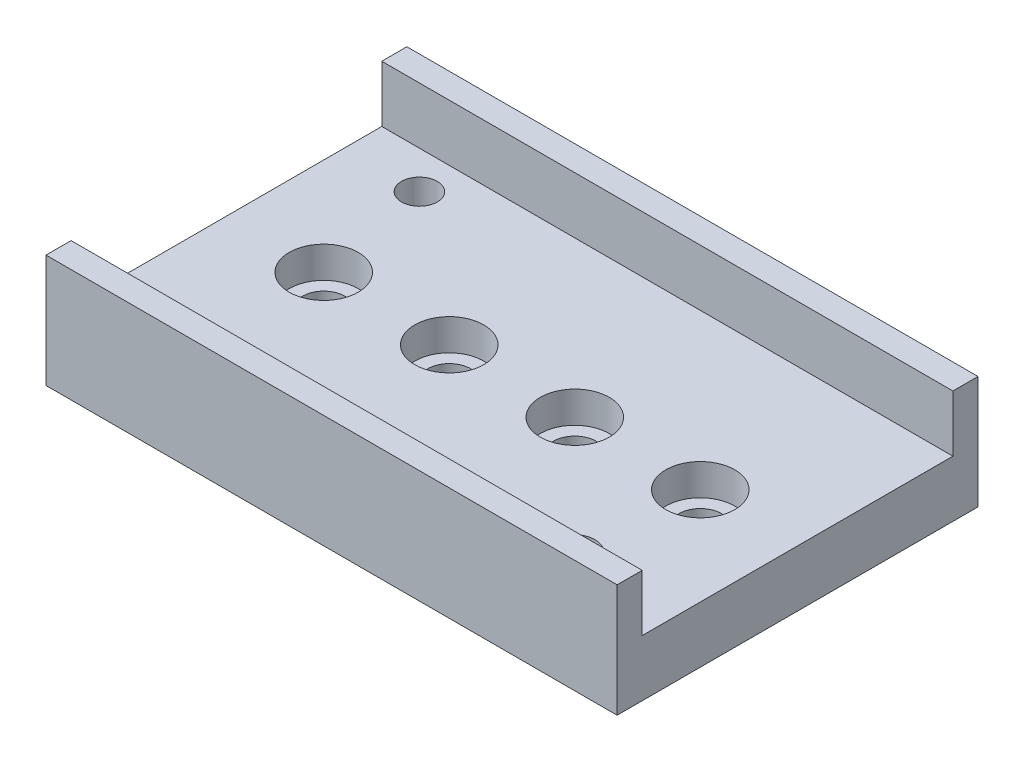
SolidWorks part; units mm, degrees
ref_plane "Front Plane" through (0, 0, 0) normal (0, 0, 1) x (1, 0, 0)
ref_plane "Top Plane" through (0, 0, 0) normal (0, 1, 0) x (1, 0, 0)
ref_plane "Right Plane" through (0, 0, 0) normal (1, 0, 0) x (0, 0, -1)
sketch "Sketch1" plane through (0, 0, 0) normal (0, 1, 0) x (1, 0, 0)
  line L0 (-22.75, 14.375) -> (22.75, 14.375)
  line L1 (-20.75, -12.375) -> (20.75, -12.375)
  line L2 (-20.75, -12.375) -> (-20.75, 12.375)
  line L3 (-20.75, 12.375) -> (20.75, 12.375)
  line L4 (20.75, -12.375) -> (20.75, 12.375)
  line L5 (-20.75, -12.375) -> (20.75, 12.375) construction
  line L6 (-20.75, 12.375) -> (20.75, -12.375) construction
  line L7 (22.75, -14.375) -> (22.75, 14.375)
  line L8 (-22.75, -14.375) -> (22.75, -14.375)
  line L9 (-22.75, -14.375) -> (-22.75, 14.375)
  circle A1 centre (-15, 0) radius 1.7
  circle A2 centre (-5, 0) radius 1.7
  circle A3 centre (5, 0) radius 1.7
  circle A4 centre (15, 0) radius 1.7
  point P0 (0, 0)
  dimension "D4" = 3.4
  dimension "D5" = 7.75
  dimension "D7" = 10
  dimension "D1" = 24.75
  dimension "D2" = 41.5
  dimension "D3" = 2
  dimension "D6" = 4
extrude "Boss-Extrude1" add sketch "Sketch1" along normal blind 2 contours L1 L4 L3 L2 | L9 L8 L7 L0 L4 L1 L2 L3
sketch "Sketch2" plane through (0, 2, 0) normal (0, 1, 0) x (1, 0, 0)
  line L1 (-22.75, -14.375) -> (22.75, -14.375) construction
  line L2 (-22.75, 14.375) -> (22.75, 14.375)
  line L3 (-22.75, 14.375) -> (-22.75, 12.375)
  line L4 (-22.75, -14.375) -> (22.75, -14.375)
  line L5 (22.75, 14.375) -> (22.75, 12.375)
  line L6 (22.75, -14.375) -> (22.75, 14.375) construction
  line L8 (-20.75, -12.375) -> (20.75, -12.375)
  line L10 (-20.75, 12.375) -> (20.75, 12.375)
  line L11 (-20.75, 12.375) -> (-22.75, 12.375)
  line L12 (-20.75, -12.375) -> (-22.75, -12.375)
  line L13 (-22.75, -12.375) -> (-22.75, -14.375)
  line L14 (-22.75, 14.375) -> (-22.75, -14.375) construction
  line L15 (-20.75, 12.375) -> (-20.75, -12.375) construction
  line L16 (20.75, 12.375) -> (22.75, 12.375)
  line L17 (20.75, -12.375) -> (22.75, -12.375)
  line L18 (22.75, -12.375) -> (22.75, -14.375)
  line L19 (20.75, 12.375) -> (20.75, -12.375) construction
  line L20 (22.75, 14.375) -> (22.75, -14.375) construction
  dimension "D1" = 2
extrude "Boss-Extrude2" add sketch "Sketch2" along normal blind 7
sketch "Sketch3" plane through (0, 2, 0) normal (0, 1, 0) x (1, 0, 0)
  line L0 (22.75, -12.375) -> (22.75, 12.375) construction
  line L1 (-22.75, 12.375) -> (22.75, 12.375)
  line L2 (-22.75, 12.375) -> (-22.75, 4.375)
  line L3 (-22.75, 4.375) -> (22.75, 4.375)
  line L4 (22.75, 12.375) -> (22.75, 4.375)
  line L6 (-22.75, -12.375) -> (22.75, -12.375)
  line L7 (-22.75, -12.375) -> (-22.75, -4.375)
  line L8 (-22.75, -4.375) -> (22.75, -4.375)
  line L9 (22.75, -12.375) -> (22.75, -4.375)
  line L12 (-22.75, 4.375) -> (22.75, 4.375)
  line L13 (-22.75, 4.375) -> (-22.75, -4.375)
  line L14 (-22.75, 0) -> (22.75, 0) construction
  line L15 (-22.75, -12.375) -> (-22.75, 12.375) construction
  line L16 (-22.75, -4.375) -> (22.75, -4.375)
  line L17 (22.75, 4.375) -> (22.75, -4.375)
  circle A2 centre (-16.75, 9.375) radius 1.425
  circle A3 centre (14.25, -9.325) radius 1.685
  circle A5 centre (-15, 0) radius 2.75
  circle A6 centre (-5, 0) radius 2.75
  circle A7 centre (5, 0) radius 2.75
  circle A8 centre (15, 0) radius 2.75
  line M22 (-22.75, 12.375) -> (-22.75, -12.375)
  line M23 (-22.75, -12.375) -> (22.75, -12.375)
  line M24 (22.75, -12.375) -> (22.75, 12.375)
  line M25 (22.75, 12.375) -> (-22.75, 12.375)
  dimension "D3" = 18.7
  dimension "D5" = 3
  dimension "D6" = 6
  dimension "D7" = 2.85
  dimension "D8" = 5.5
  dimension "D1" = 8
  dimension "D2" = 8
  dimension "D4" = 31
  dimension "D9" = 4
extrude "Boss-Extrude3" add sketch "Sketch3" along normal blind 2.5 contours L3 A2 M22 M24 M25 | L14 A5 A6 A7 A8 L17 L3 M22 | L14 L13 L8 A8 A7 A6 A5 M24 | L8 A3 M22 M23 M24
sketch "Sketch4" plane through (0, 2, 0) normal (0, 1, 0) x (1, 0, 0)
  line L1 (-19.8677, 9.375) -> (-18.3088, 6.675)
  line L2 (-18.3088, 6.675) -> (-15.1912, 6.675)
  line L3 (-15.1912, 6.675) -> (-13.6323, 9.375)
  line L4 (-13.6323, 9.375) -> (-15.1912, 12.075)
  line L5 (-15.1912, 12.075) -> (-18.3088, 12.075)
  line L6 (-18.3088, 12.075) -> (-19.8677, 9.375)
  line L7 (14.4956, -6.217) -> (11.6812, -7.5583)
  line L8 (11.6812, -7.5583) -> (11.4356, -10.6663)
  line L9 (11.4356, -10.6663) -> (14.0044, -12.433)
  line L10 (14.0044, -12.433) -> (16.8188, -11.0917)
  line L11 (16.8188, -11.0917) -> (17.0644, -7.9837)
  line L12 (17.0644, -7.9837) -> (14.4956, -6.217)
  circle A0 centre (-16.75, 9.375) radius 2.7 construction
  circle A1 centre (14.25, -9.325) radius 2.7 construction
  dimension "D1" = 5.4
extrude "Cut-Extrude1" cut sketch "Sketch4" against normal up to next
